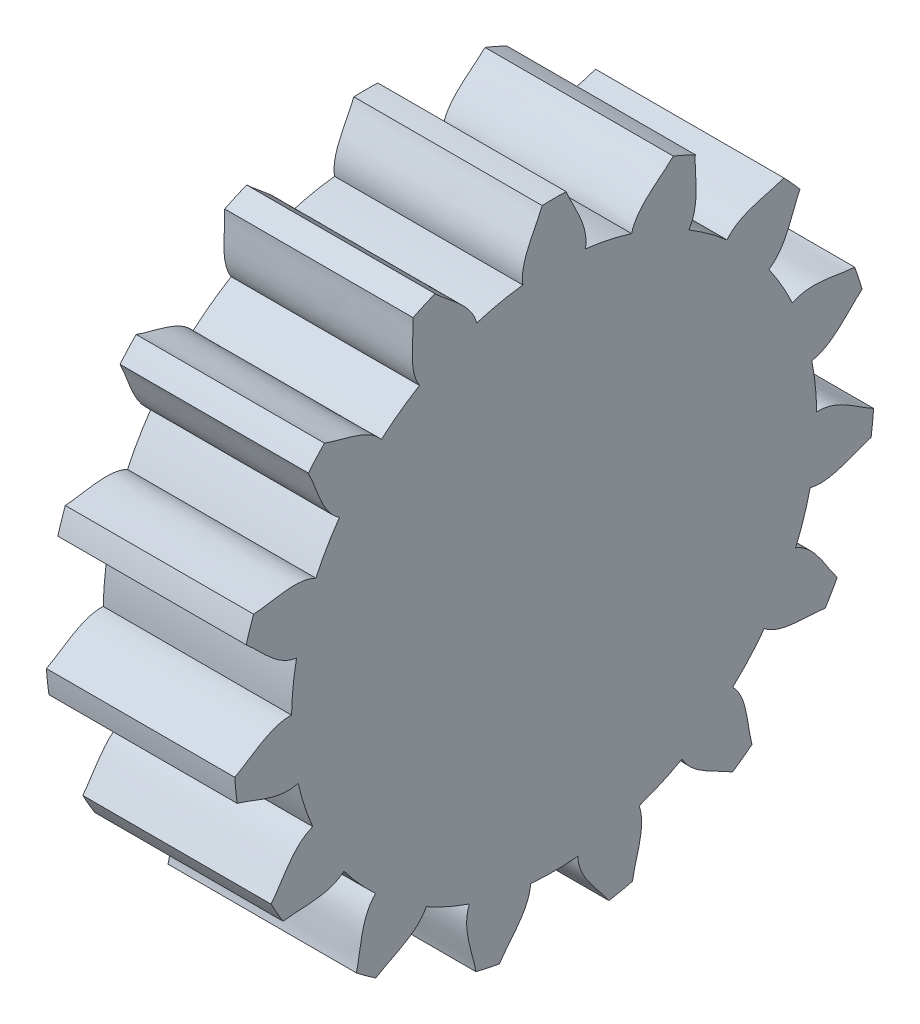
SolidWorks part; units mm, degrees
ref_plane "Front Plane" through (0, 0, 0) normal (1, 0, 0) x (0, 1, 0)
ref_plane "Top Plane" through (0, 0, 0) normal (0, 0, 1) x (0, 1, 0)
ref_plane "Right Plane" through (0, 0, 0) normal (0, 1, 0) x (-1, 0, 0)
sketch "Sketch1" plane through (0, 0, 0) normal (1, 0, 0) x (0, 1, 0)
  line L0 (0, 0) -> (0, 20.5212) construction
  line L1 (-16.6548, 15) -> (16.6548, 15) construction
  line L2 (13.5164, 19.9196) -> (-18.6299, 8.2193) construction
  line L3 (0, 0) -> (-4.8209, 13.2453) construction
  line L4 (-8.7345, 11.063) -> (-1.176, 17.0306) construction
  line L5 (-0.9196, 14.0654) -> (0.2083, 14.1391) construction
  circle A0 centre (0, 0) radius 15
  circle A1 centre (0, 0) radius 14.0954 construction
  arc A2 (-4.8209, 13.2453) -> (-8.7345, 11.063) centre (0, 0) ccw
  arc A3 (-4.8209, 13.2453) -> (-0.9196, 14.0654) centre (0, 0) cw
  point P7 (0, 15)
  point P14 (0.2098, 14.0938)
  dimension "D1" = 30
  dimension "D2" = 20
  dimension "D3" = 5.1303
  dimension "D5" = 9.6303
  dimension "D7" = 1.1303
  dimension "D4" = 4.5
  dimension "D6" = 4
  dimension "D8" = 5.13
sketch "Sketch2" plane through (0, 0, 0) normal (1, 0, 0) x (0, 1, 0)
  line L0 (0, 0) -> (-2.0166, 19.1865) construction
  line L1 (0, 0) -> (0, 20.5212) construction
  line L2 (-3.2797, 13.5769) -> (0.3852, 13.9621) construction
  circle A0 centre (0, 0) radius 17
  arc A14 (-0.9196, 14.0654) -> (-4.8209, 13.2453) centre (0, 0) ccw construction
  spline S0 degree 3 poles (-1.1415, 16.9616) (-0.8369, 16.3692) (-0.0852, 15.4534) (0.1995, 14.4191) (0.2111, 14.0591) (0.2099, 13.9938) (0.2069, 13.9434) knots 0.026838 0.026838 0.026838 0.026838 0.715933 0.98618 1 1.045668 1.045668 1.045668 1.045668
  spline S1 degree 3 poles (-2.41, 16.8283) (-2.5848, 16.1855) (-3.1296, 15.1334) (-3.1931, 14.0625) (-3.1295, 13.708) (-3.1147, 13.6443) (-3.1013, 13.5957) knots 0.026838 0.026838 0.026838 0.026838 0.715933 0.98618 1 1.045668 1.045668 1.045668 1.045668
  point P21 (-1.4472, 13.7695)
  dimension "D2" = 34
  dimension "D1" = 6
  dimension "D3" = 0.25
sketch "Sketch3" plane through (0, 0, 0) normal (1, 0, 0) x (0, 1, 0)
  circle A0 centre (0, 0) radius 17 construction
  arc A1 (-1.1415, 16.9616) -> (-2.41, 16.8283) centre (0, 0) ccw
  arc A2 (-3.1013, 13.5957) -> (0.2069, 13.9434) centre (0, 0) ccw
  spline S0 degree 3 poles (2997.0397, -84.0704) (-162.8718, 24.9273) (-0.2576, 28.71) (0.6323, 0.8915) (-135.0867, -27.3662) (-2999.2121, -5.9316) knots -12.371432 -12.371432 -12.371432 -12.371432 0.98618 1 13.104315 13.104315 13.104315 13.104315 only from (-1.1415, 16.9616) to (0.2069, 13.9434) construction
  spline S1 degree 3 poles (-2914.068, -705.3528) (154.13, 58.2455) (-5.7171, 28.1362) (-0.8038, 0.7405) (137.8245, 1.3179) (2934.9054, 617.7693) knots -12.371432 -12.371432 -12.371432 -12.371432 0.98618 1 13.104315 13.104315 13.104315 13.104315 only from (-2.41, 16.8283) to (-3.1013, 13.5957) construction
  spline S2 degree 3 poles (-1.1415, 16.9616) (-0.6911, 16.0857) (0.2737, 15.0668) (0.2069, 13.9434) knots 0.026838 0.026838 0.026838 0.026838 1.045668 1.045668 1.045668 1.045668
  spline S3 degree 3 poles (-2.41, 16.8283) (-2.6684, 15.8779) (-3.4003, 14.6807) (-3.1013, 13.5957) knots 0.026838 0.026838 0.026838 0.026838 1.045668 1.045668 1.045668 1.045668
extrude "Boss-Extrude1" add sketch "Sketch3" along normal blind 10
pattern_circular "CirPattern1" count 15 over 360 about axis through (10, 0, 0) along (1, 0, 0) of "Boss-Extrude1"
equation "\"D5@Sketch1\"=\"D3@Sketch1\"+\"D4@Sketch1\""
equation "\"D7@Sketch1\"=\"D3@Sketch1\"-\"D6@Sketch1\""
